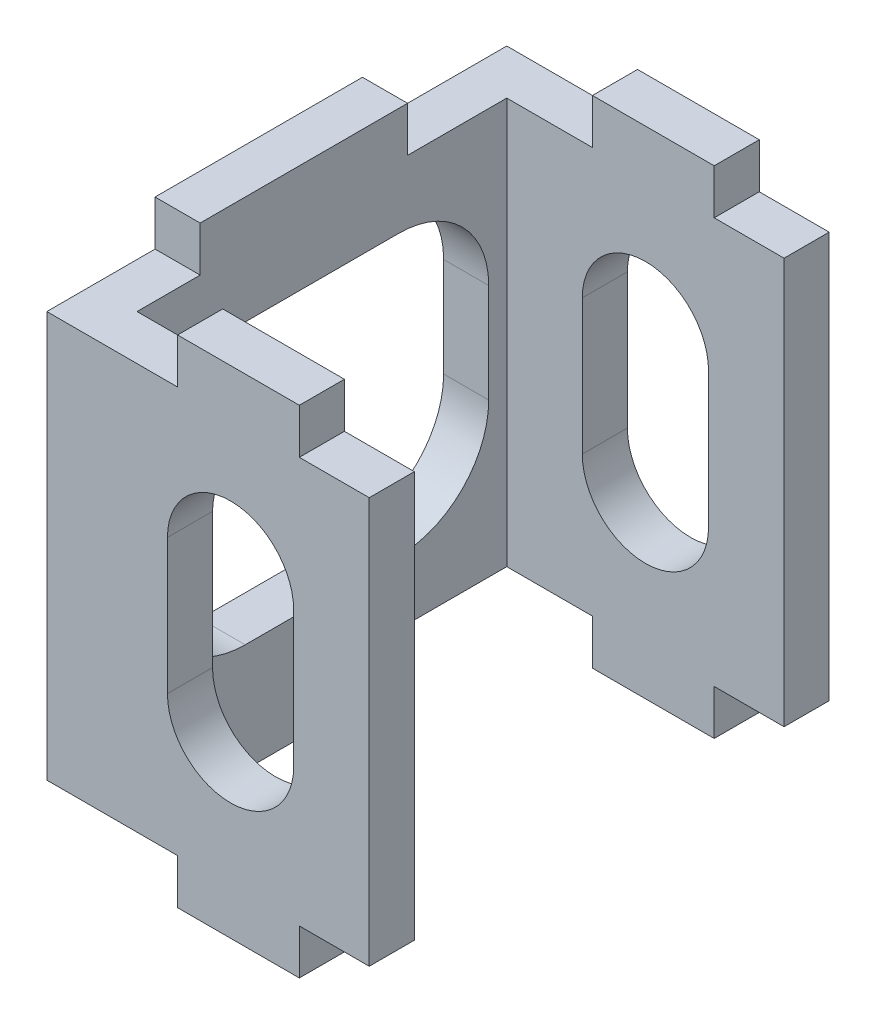
SolidWorks part; units mm, degrees
ref_plane "Plan de face" through (0, 0, 0) normal (0, 0, 1) x (1, 0, 0)
ref_plane "Plan de dessus" through (0, 0, 0) normal (0, 1, 0) x (1, 0, 0)
ref_plane "Plan de droite" through (0, 0, 0) normal (1, 0, 0) x (0, 0, -1)
sketch "Esquisse1" plane through (0, 0, 0) normal (0, 1, 0) x (1, 0, 0)
  line L1 (21.25, 23.75) -> (-21.25, 23.75)
  line L2 (21.25, 23.75) -> (21.25, -23.75)
  line L3 (21.25, -23.75) -> (-21.25, -23.75)
  line L4 (-21.25, 23.75) -> (-21.25, -23.75)
  line L5 (21.25, 23.75) -> (-21.25, -23.75) construction
  line L6 (21.25, -23.75) -> (-21.25, 23.75) construction
  point P0 (0, 0)
  dimension "D1" = 47.5
  dimension "D2" = 42.5
extrude "Extru.-Mince1" add sketch "Esquisse1" along normal blind 20 thin
sketch "Esquisse3" plane through (0, 0, 0) normal (0, -1, 0) x (1, 0, 0)
  line L0 (26.25, 28.75) -> (38, 28.75)
  line L1 (38, 28.75) -> (38, -22.25)
  line L3 (38, -22.25) -> (21.25, -22.25)
  line L4 (21.25, 23.75) -> (21.25, -23.75) construction
  line L5 (26.25, 28.75) -> (0, 28.75)
  line L6 (0, 28.75) -> (-26.25, 28.75)
  line L7 (-26.25, 28.75) -> (-62, 28.75)
  line L8 (-62, 28.75) -> (-62, -22.25)
  line L9 (-62, -22.25) -> (-21.25, -22.25)
  line L10 (-26.25, -28.75) -> (-26.25, 28.75) construction
  line L11 (33, 23.75) -> (33, -17.25)
  line L12 (33, -17.25) -> (26.25, -17.25)
  line L13 (26.25, 28.75) -> (26.25, -28.75) construction
  line L14 (26.25, -17.25) -> (26.25, 23.75)
  line L15 (26.25, 23.75) -> (33, 23.75)
  line L16 (-57, -17.25) -> (-26.25, -17.25)
  line L17 (-21.25, -23.75) -> (-21.25, 23.75) construction
  line L18 (-57, -17.25) -> (-57, 23.75)
  line L19 (-57, 23.75) -> (-26.25, 23.75)
  line L20 (-21.25, 23.75) -> (21.25, 23.75)
  line L21 (21.25, 23.75) -> (21.25, -22.25)
  line L22 (-21.25, 23.75) -> (-21.25, -22.25)
  line L23 (-26.25, 23.75) -> (-26.25, -17.25)
  line L24 (-26.25, 28.75) -> (26.25, 28.75) construction
  point P6 (26.25, 28.75)
  point P7 (-26.25, 28.75)
  dimension "D1" = 51
  dimension "D2" = 38
  dimension "D3" = 62
  dimension "D4" = 5
  dimension "D5" = 5
  dimension "D6" = 5
  dimension "D7" = 5
  dimension "D8" = 5
  dimension "D9" = 5
extrude "Boss.-Extru.1" add sketch "Esquisse3" against normal blind 45
sketch "Esquisse6" plane through (0, 45, 0) normal (0, 1, 0) x (1, 0, 0)
  line L0 (38, 6.25) -> (33, 6.25)
  line L1 (38, 22.25) -> (38, -28.75) construction
  line L2 (33, 17.25) -> (33, -23.75) construction
  line L3 (33, 6.25) -> (33, -16.75)
  line L4 (33, -16.75) -> (38, -16.75)
  line L5 (38, -16.75) -> (38, 6.25)
  line L6 (23, -28.75) -> (23, -23.75)
  line L7 (38, -28.75) -> (-62, -28.75) construction
  line L8 (33, -23.75) -> (26.25, -23.75) construction
  line L9 (23, -23.75) -> (9.5, -23.75)
  line L10 (-21.25, -23.75) -> (21.25, -23.75) construction
  line L11 (9.5, -23.75) -> (9.5, -28.75)
  line L12 (9.5, -28.75) -> (23, -28.75)
  line L13 (-5.5, -28.75) -> (-5.5, -23.75)
  line L14 (-5.5, -23.75) -> (-19, -23.75)
  line L15 (-19, -23.75) -> (-19, -28.75)
  line L16 (-19, -28.75) -> (-5.5, -28.75)
  line L17 (-34, -28.75) -> (-34, -23.75)
  line L18 (-34, -23.75) -> (-47.5, -23.75)
  line L19 (-47.5, -23.75) -> (-47.5, -28.75)
  line L20 (-47.5, -28.75) -> (-34, -28.75)
  line L23 (-47.5, 22.25) -> (-34, 22.25)
  line L24 (-47.5, 17.25) -> (-47.5, 22.25)
  line L25 (-34, 17.25) -> (-47.5, 17.25)
  line L26 (-34, 22.25) -> (-34, 17.25)
  line L28 (-62, -16.75) -> (-62, 6.25)
  line L29 (-57, -16.75) -> (-62, -16.75)
  line L30 (-57, 6.25) -> (-57, -16.75)
  line L31 (-62, 6.25) -> (-57, 6.25)
  point P6 (38, -5.25)
  point P15 (38, -5.25)
  dimension "D1" = 23
  dimension "D2" = 13.5
  dimension "D3" = 15
  dimension "D5" = 23.5
  dimension "D6" = 12
  dimension "D4" = 3
extrude "Boss.-Extru.3" add sketch "Esquisse6" along normal blind 5
sketch "Esquisse2" plane through (0, 0, 28.75) normal (0, 0, 1) x (1, 0, 0)
  line L0 (-62, 0) -> (38, 0) construction
  line L1 (0, -0.0585) -> (0, 20) construction
  line L2 (-15.5, 5.2) -> (15.5, 5.2) construction
  line L3 (38, 45) -> (38, 0) construction
  line L4 (0, 36.2159) -> (0, 28.8659) construction
  line L5 (2.65, 36.2159) -> (2.65, 32.2159)
  line L6 (-62, 0) -> (38, 0) construction
  line L7 (0, 20) -> (33.7261, 20) construction
  line L8 (-15.5, 34.8) -> (15.5, 34.8) construction
  line L9 (-2.65, 36.2159) -> (-2.65, 32.2159)
  arc A0 (-2.65, 32.2159) -> (2.65, 32.2159) centre (0, 20) ccw
  circle A1 centre (-15.5, 5.2) radius 1.6
  circle A2 centre (15.5, 5.2) radius 1.6
  circle A3 centre (15.5, 34.8) radius 1.6
  circle A4 centre (-15.5, 34.8) radius 1.6
  arc A5 (2.65, 36.2159) -> (-2.65, 36.2159) centre (0, 36.2159) ccw
  point P6 (0, -0.0585)
  point P10 (0, 5.2)
  point P20 (0, 34.8)
  point P21 (0, 40.0585)
  point P24 (0, 32.5)
  dimension "D2" = 25
  dimension "D3" = 3.2
  dimension "D4" = 3.2
  dimension "D8" = 2.65
  dimension "D1" = 20
  dimension "D5" = 5.2
  dimension "D6" = 31
  dimension "D7" = 38
  dimension "D9" = 7.35
  dimension "D10" = 5.3
  dimension "D11" = 4
extrude "Enlèv. mat.-Extru.1" cut sketch "Esquisse2" against normal up to next
sketch "Esquisse4" plane through (0, 0, 23.75) normal (0, 0, -1) x (-1, 0, 0)
  line L0 (-12.5, 20) -> (-12.5, 50)
  line L2 (-23, 50) -> (-9.5, 50) construction
  line L3 (12.5, 50) -> (12.5, 20)
  line L4 (-12.5, 50) -> (12.5, 50)
  circle A0 centre (0, 20) radius 12.5 construction
  arc A1 (-12.5, 20) -> (12.5, 20) centre (0, 20) cw
  dimension "D1" = 25
extrude "Enlèv. mat.-Extru.2" cut sketch "Esquisse4" against normal blind 3
ref_plane "Plan1" through (0, 22.5, 0) normal (0, -1, 0) x (-1, 0, 0)
mirror "Symétrie1" about plane through (0, 22.5, 0) normal (0, -1, 0) of "Boss.-Extru.3"
ref_plane "Plan2" through (0, 0, 0) normal (1, 0, 0) x (0, 0, -1)
fillet "Congé1" radius 3 1 edges at (0, 20, -23.75)
sketch "Esquisse7" plane through (38, 0, 0) normal (1, 0, 0) x (0, 0, -1)
  line L0 (-16.75, 0) -> (-28.75, 0) construction
  line L1 (-11.75, 38) -> (5.25, 38)
  line L2 (-21.75, 28) -> (-21.75, 17)
  line L3 (-11.75, 7) -> (5.25, 7)
  line L4 (15.25, 28) -> (15.25, 17)
  line L5 (-21.75, 38) -> (15.25, 7) construction
  line L6 (-21.75, 7) -> (15.25, 38) construction
  line L7 (-16.75, 45) -> (-28.75, 45) construction
  line L8 (22.25, 45) -> (22.25, 0) construction
  line L9 (-28.75, 45) -> (-28.75, 0) construction
  arc A0 (5.25, 7) -> (15.25, 17) centre (5.25, 17) ccw
  arc A1 (-21.75, 17) -> (-11.75, 7) centre (-11.75, 17) ccw
  arc A2 (5.25, 38) -> (15.25, 28) centre (5.25, 28) cw
  arc A3 (-11.75, 38) -> (-21.75, 28) centre (-11.75, 28) ccw
  point P0 (-3.25, 22.5)
  dimension "D5" = 10
  dimension "D1" = 7
  dimension "D2" = 7
  dimension "D3" = 7
  dimension "D4" = 7
extrude "Enlèv. mat.-Extru.3" cut sketch "Esquisse7" against normal through all
sketch "Esquisse8" plane through (0, 0, -22.25) normal (0, 0, -1) x (-1, 0, 0)
  line L0 (41.625, 30) -> (41.625, 15) construction
  line L1 (48.625, 30) -> (48.625, 15)
  line L2 (34.625, 30) -> (34.625, 15)
  line L3 (62, 45) -> (62, 0) construction
  line L5 (62, 22.5) -> (21.25, 22.5) construction
  line L6 (21.25, 45) -> (21.25, 20) construction
  arc A0 (48.625, 30) -> (34.625, 30) centre (41.625, 30) ccw
  arc A1 (34.625, 15) -> (48.625, 15) centre (41.625, 15) ccw
  point P2 (41.625, 22.5)
  dimension "D2" = 7
  dimension "D1" = 15
extrude "Enlèv. mat.-Extru.4" cut sketch "Esquisse8" against normal through all
sketch "Esquisse10" plane through (0, 45, 0) normal (0, 1, 0) x (1, 0, 0)
  line L0 (-26.25, -28.75) -> (-26.25, 22.25)
  line L1 (-19, -28.75) -> (-34, -28.75) construction
  line L2 (-34, 22.25) -> (-21.25, 22.25) construction
  line L3 (-26.25, 22.25) -> (-62, 22.25)
  line L4 (-62, 22.25) -> (-62, -28.75)
  line L5 (-62, -28.75) -> (-26.25, -28.75)
  line L6 (-26.25, 17.25) -> (-26.25, -23.75) construction
  point P6 (-26.25, -3.25)
  point P17 (-26.25, -3.25)
sketch "Esquisse11" plane through (0, 45, 0) normal (0, 1, 0) x (1, 0, 0)
  line L0 (38, -28.75) -> (-26.25, -28.75)
  line L1 (-26.25, -28.75) -> (-26.25, 43.6346)
  line L2 (-26.25, 43.6346) -> (38, 43.6346)
  line L3 (38, 43.6346) -> (38, -28.75)
extrude "Enlèv. mat.-Extru.5" cut sketch "Esquisse11" against normal through all both and the other way through all
